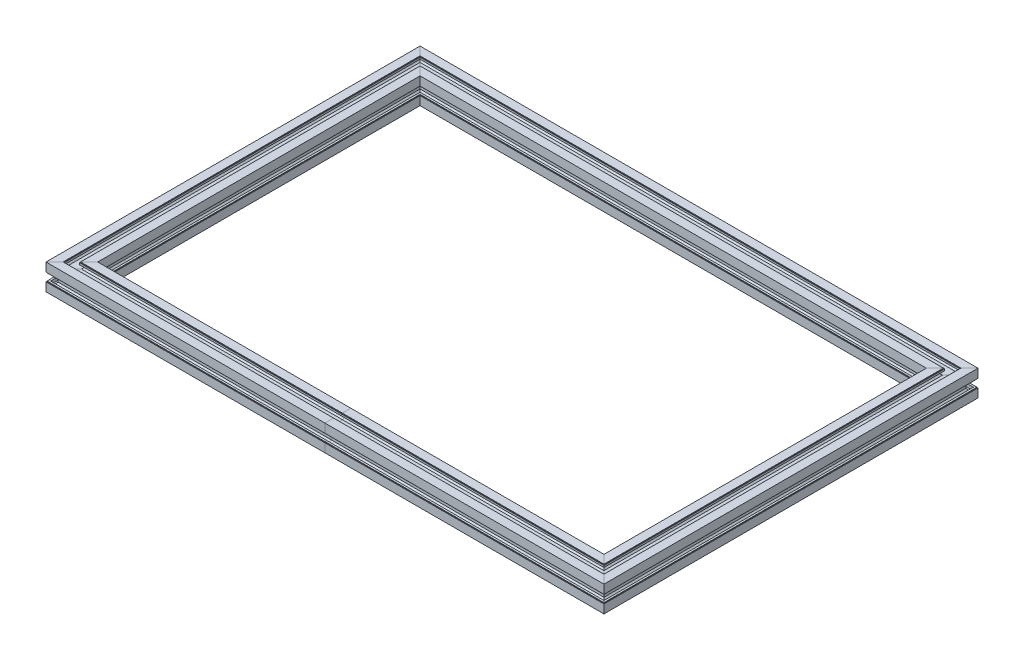
SolidWorks part; units mm, degrees
ref_plane "Alzado" through (0, 0, 0) normal (0, 0, 1) x (1, 0, 0)
ref_plane "Planta" through (0, 0, 0) normal (0, 1, 0) x (1, 0, 0)
ref_plane "Vista lateral" through (0, 0, 0) normal (1, 0, 0) x (0, 0, -1)
sketch "Croquis1" plane through (0, 0, 0) normal (0, 1, 0) x (1, 0, 0)
  line L0 (-200.934, 131.5) -> (200.934, 131.5)
  line L1 (-200.934, 131.5) -> (-200.934, -131.5)
  line L2 (-200.934, -131.5) -> (200.934, -131.5)
  line L3 (200.934, 131.5) -> (200.934, -131.5)
  line L4 (-200.934, 131.5) -> (200.934, -131.5) construction
  line L5 (-200.934, -131.5) -> (200.934, 131.5) construction
  point P0 (0, 0)
  dimension "D1" = 263
  dimension "D2" = 401.868
sketch "Croquis2" plane through (0, 0, 0) normal (1, 0, 0) x (0, 0, -1)
  line L0 (-134.8497, 9.7506) -> (-134.8497, 9.3906)
  line L1 (-131.5, 12.2683) -> (-131.5, -11.1064) construction
  line L2 (-142.7355, 0) -> (-118.6195, 0) construction
  line L3 (-121.7492, 3.1854) -> (-122.1092, 3.1852)
  line L4 (-141.2508, 3.1854) -> (-141.2508, 9.7506)
  line L5 (-122.1092, 3.1852) -> (-122.1089, 2.6802)
  line L6 (-122.1089, 2.6802) -> (-123.4789, 2.6794)
  line L7 (-134.8497, 9.3906) -> (-134.3447, 9.3906)
  line L8 (-134.3447, 9.3906) -> (-134.3447, 8.0206)
  line L9 (-134.3447, 8.0206) -> (-136.6797, 8.0206)
  line L10 (-136.6797, 8.0206) -> (-136.6797, 6.7206)
  line L11 (-136.6797, 6.7206) -> (-135.1232, 5.1632)
  line L12 (-123.4789, 2.6794) -> (-123.4803, 5.0143)
  line L13 (-123.4803, 5.0143) -> (-124.7803, 5.0136)
  line L14 (-141.2508, 9.7506) -> (-134.8497, 9.7506)
  line L15 (-124.7803, 5.0136) -> (-126.3367, 3.4561)
  line L16 (-121.7492, 9.7506) -> (-128.1503, 9.7506)
  line L17 (-138.2197, 5.0136) -> (-136.6633, 3.4561)
  line L18 (-139.5197, 5.0143) -> (-138.2197, 5.0136)
  line L19 (-139.5211, 2.6794) -> (-139.5197, 5.0143)
  line L20 (-140.8911, 2.6802) -> (-139.5211, 2.6794)
  line L21 (-140.8908, 3.1852) -> (-140.8911, 2.6802)
  line L22 (-126.3203, 6.7206) -> (-127.8768, 5.1632)
  line L23 (-141.2508, 3.1854) -> (-140.8908, 3.1852)
  line L24 (-126.3203, 8.0206) -> (-126.3203, 6.7206)
  line L25 (-128.6553, 8.0206) -> (-126.3203, 8.0206)
  line L26 (-128.6553, 9.3906) -> (-128.6553, 8.0206)
  line L27 (-128.1503, 9.3906) -> (-128.6553, 9.3906)
  line L28 (-121.7492, 3.1854) -> (-121.7492, 9.7506)
  line L29 (-128.1503, 9.7506) -> (-128.1503, 9.3906)
  line L30 (-141.2508, -3.1853) -> (-140.8908, -3.1851)
  line L31 (-140.8908, -3.1851) -> (-140.8911, -2.6801)
  line L32 (-140.8911, -2.6801) -> (-139.5211, -2.6793)
  line L33 (-139.5211, -2.6793) -> (-139.5197, -5.0143)
  line L34 (-139.5197, -5.0143) -> (-138.2197, -5.0135)
  line L35 (-138.2197, -5.0135) -> (-136.6633, -3.4561)
  line L36 (-141.2508, -9.7505) -> (-134.8497, -9.7505)
  line L37 (-136.6797, -6.7205) -> (-135.1232, -5.1631)
  line L38 (-136.6797, -8.0205) -> (-136.6797, -6.7205)
  line L39 (-134.3447, -8.0205) -> (-136.6797, -8.0205)
  line L40 (-134.3447, -9.3905) -> (-134.3447, -8.0205)
  line L41 (-134.8497, -9.3905) -> (-134.3447, -9.3905)
  line L42 (-141.2508, -3.1853) -> (-141.2508, -9.7505)
  line L43 (-134.8497, -9.7505) -> (-134.8497, -9.3905)
  line L44 (-128.1503, -9.7505) -> (-128.1503, -9.3905)
  line L45 (-128.1503, -9.3905) -> (-128.6553, -9.3905)
  line L46 (-128.6553, -9.3905) -> (-128.6553, -8.0205)
  line L47 (-121.7492, -3.1853) -> (-121.7492, -9.7505)
  line L48 (-128.6553, -8.0205) -> (-126.3203, -8.0205)
  line L49 (-126.3203, -8.0205) -> (-126.3203, -6.7205)
  line L50 (-126.3203, -6.7205) -> (-127.8768, -5.1631)
  line L51 (-121.7492, -9.7505) -> (-128.1503, -9.7505)
  line L52 (-124.7803, -5.0135) -> (-126.3367, -3.4561)
  line L53 (-123.4803, -5.0143) -> (-124.7803, -5.0135)
  line L54 (-123.4789, -2.6793) -> (-123.4803, -5.0143)
  line L55 (-122.1089, -2.6801) -> (-123.4789, -2.6793)
  line L56 (-122.1092, -3.1851) -> (-122.1089, -2.6801)
  line L57 (-121.7492, -3.1853) -> (-122.1092, -3.1851)
  line L58 (-136.6633, -3.4561) -> (-136.6633, 3.4561)
  line L59 (-135.1232, 5.1632) -> (-127.8768, 5.1632)
  line L60 (-126.3367, 3.4561) -> (-126.3367, -3.4561)
  line L61 (-135.1232, -5.1631) -> (-127.8768, -5.1631)
  circle A0 centre (-131.5, 0) radius 2.5
  dimension "D6" = 5
  dimension "D1" = 0.36
  dimension "D2" = 0.505
  dimension "D3" = 1.37
  dimension "D4" = 2.335
  dimension "D5" = 1.3
  dimension "D7" = 2.2019
sweep "Barrer1" add profiles "Croquis2" path "Croquis1"
